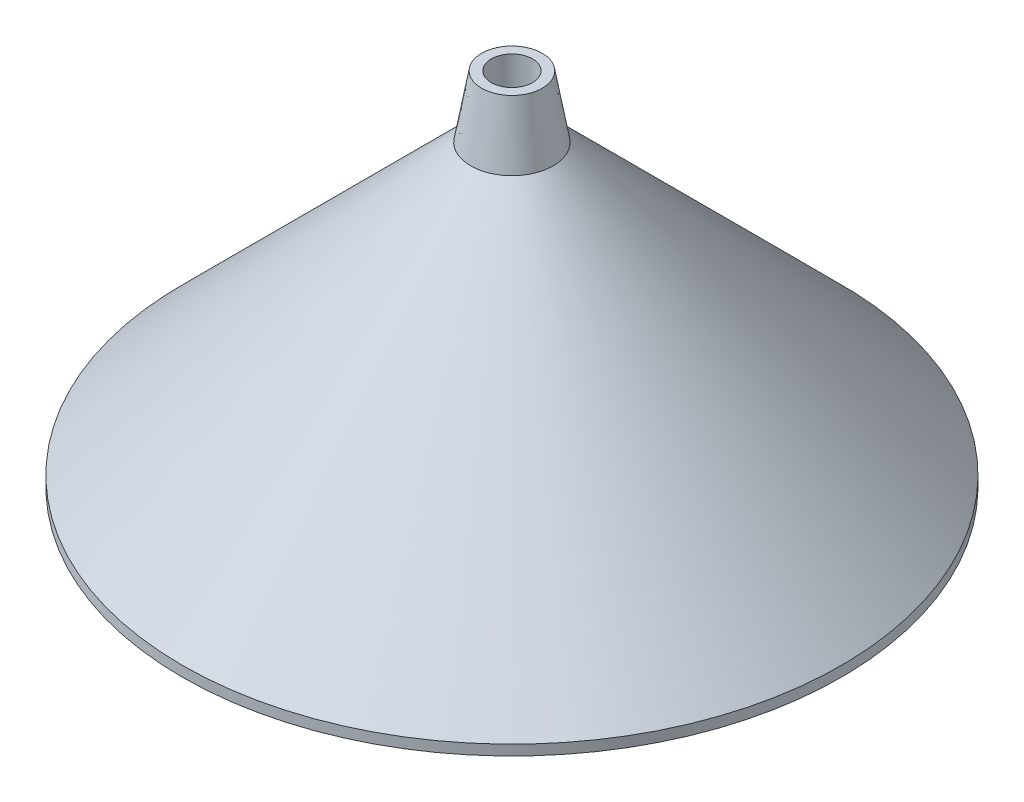
SolidWorks part; units mm, degrees
ref_plane "前视基准面" through (0, 0, 0) normal (0, 0, 1) x (1, 0, 0)
ref_plane "上视基准面" through (0, 0, 0) normal (0, 1, 0) x (1, 0, 0)
ref_plane "右视基准面" through (0, 0, 0) normal (1, 0, 0) x (0, 0, -1)
sketch "草图2" plane through (0, 0, 0) normal (0, 1, 0) x (1, 0, 0)
  circle A0 centre (0, 0) radius 32
  dimension "D1" = 64
extrude "凸台-拉伸2" add sketch "草图2" along normal blind 1
sketch "草图3" plane through (0, 1, 0) normal (0, 1, 0) x (1, 0, 0)
  circle A0 centre (0, 0) radius 32
  dimension "D1" = 64
extrude "凸台-拉伸3" add sketch "草图3" along normal blind 28 draft 45
sketch "草图5" plane through (0, 0, 0) normal (0, -1, 0) x (-1, 0, 0)
  circle A0 centre (0, 0) radius 30
  dimension "D1" = 60
extrude "切除-拉伸1" cut sketch "草图5" against normal blind 1
sketch "草图6" plane through (0, 1, 0) normal (0, -1, 0) x (-1, 0, 0)
  circle A0 centre (0, 0) radius 30
  dimension "D1" = 60
extrude "切除-拉伸2" cut sketch "草图6" against normal blind 28 draft 45
sketch "草图7" plane through (0, 29, 0) normal (0, 1, 0) x (1, 0, 0)
  circle A1 centre (0, 0) radius 4
  dimension "D2" = 8
extrude "凸台-拉伸5" add sketch "草图7" along normal blind 6 draft 10
sketch "草图10" plane through (0, 29, 0) normal (0, -1, 0) x (-1, 0, 0)
  circle A0 centre (0, 0) radius 2
  dimension "D1" = 4
extrude "切除-拉伸3" cut sketch "草图10" against normal through all
